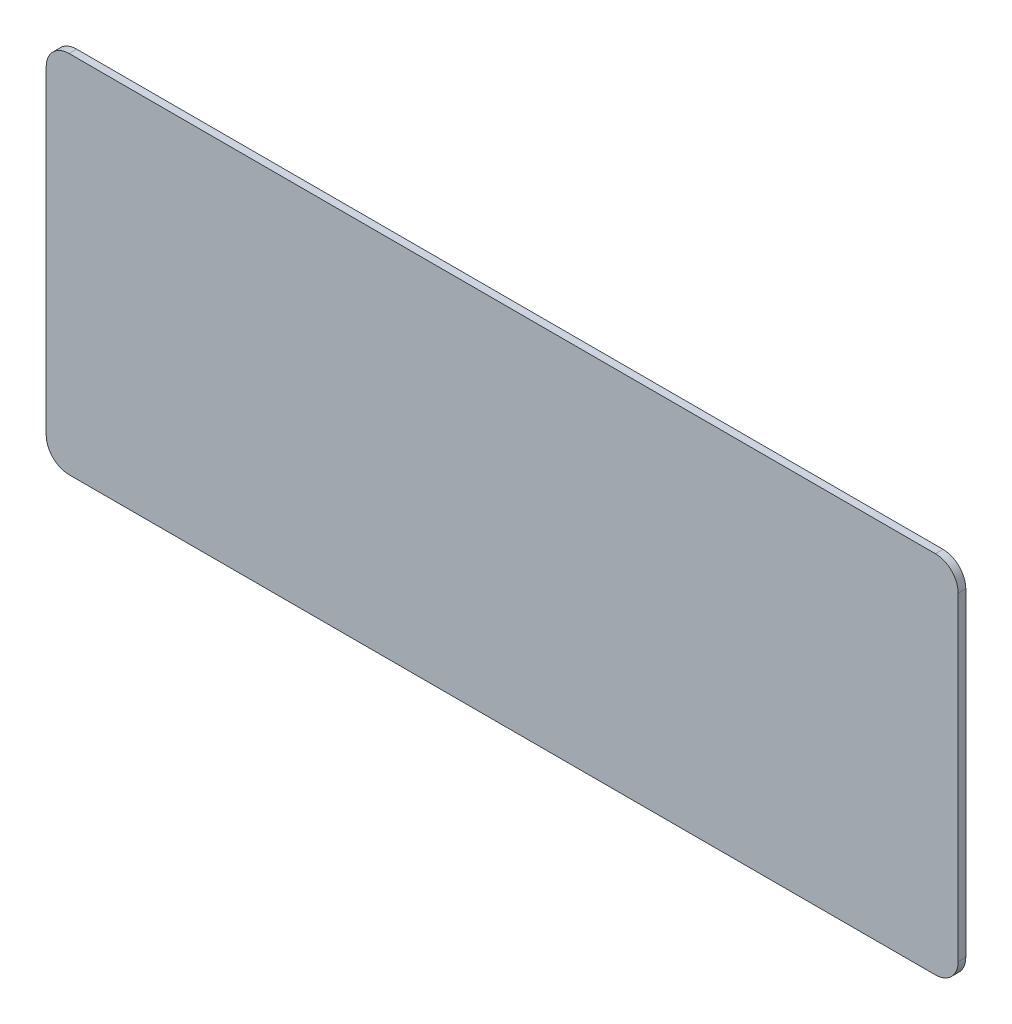
SolidWorks part; units mm, degrees
ref_plane "Front Plane" through (0, 0, 0) normal (0, 0, 1) x (1, 0, 0)
ref_plane "Top Plane" through (0, 0, 0) normal (0, 1, 0) x (1, 0, 0)
ref_plane "Right Plane" through (0, 0, 0) normal (1, 0, 0) x (0, 0, -1)
sketch "Sketch1" plane through (0, 0, 0) normal (0, 0, 1) x (1, 0, 0)
  line L5 (-51.9401, -23.8056) -> (62.0599, -23.8056) construction
  line L6 (65.0599, -20.8056) -> (65.0599, 0.1944) construction
  line L13 (-54.9401, 0.1944) -> (-54.9401, -20.8056) construction
  line L14 (65.0599, 0.1944) -> (65.0599, 21.1944) construction
  line L15 (62.0599, 24.1944) -> (-51.9401, 24.1944) construction
  line L16 (-54.9401, 21.1944) -> (-54.9401, 0.1944) construction
  line L22 (-51.9401, -23.8056) -> (62.0599, -23.8056)
  line L23 (65.0599, -20.8056) -> (65.0599, 0.1944)
  line L29 (-54.9401, 0.1944) -> (-54.9401, -20.8056)
  line L30 (65.0599, 0.1944) -> (65.0599, 21.1944)
  line L31 (62.0599, 24.1944) -> (-51.9401, 24.1944)
  line L32 (-54.9401, 21.1944) -> (-54.9401, 0.1944)
  arc A0 (62.0599, -23.8056) -> (65.0599, -20.8056) centre (62.0599, -20.8056) ccw construction
  arc A3 (-54.9401, -20.8056) -> (-51.9401, -23.8056) centre (-51.9401, -20.8056) ccw construction
  arc A4 (65.0599, 21.1944) -> (62.0599, 24.1944) centre (62.0599, 21.1944) ccw construction
  arc A5 (-51.9401, 24.1944) -> (-54.9401, 21.1944) centre (-51.9401, 21.1944) ccw construction
  arc A8 (62.0599, -23.8056) -> (65.0599, -20.8056) centre (62.0599, -20.8056) ccw
  arc A11 (-54.9401, -20.8056) -> (-51.9401, -23.8056) centre (-51.9401, -20.8056) ccw
  arc A12 (65.0599, 21.1944) -> (62.0599, 24.1944) centre (62.0599, 21.1944) ccw
  arc A13 (-51.9401, 24.1944) -> (-54.9401, 21.1944) centre (-51.9401, 21.1944) ccw
extrude "Boss-Extrude1" add sketch "Sketch1" along normal blind 1
